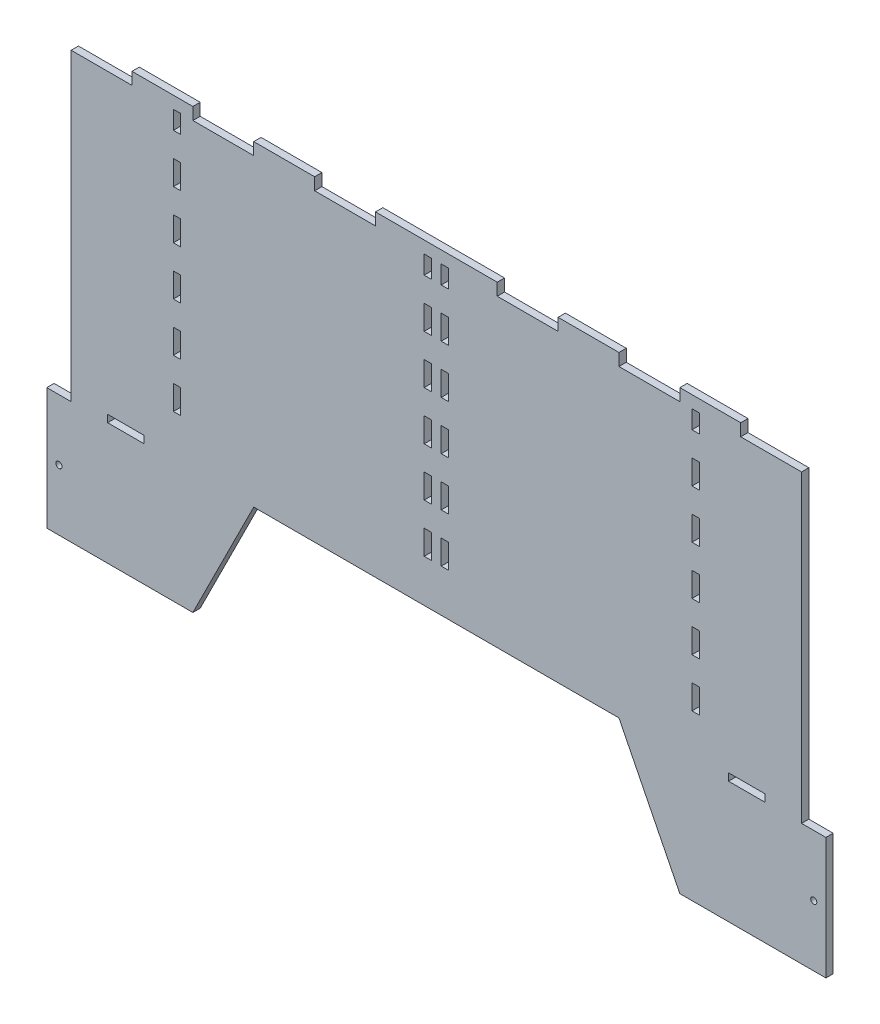
SolidWorks part; units mm, degrees
ref_plane "前视基准面" through (0, 0, 0) normal (0, 0, 1) x (1, 0, 0)
ref_plane "上视基准面" through (0, 0, 0) normal (0, 1, 0) x (1, 0, 0)
ref_plane "右视基准面" through (0, 0, 0) normal (1, 0, 0) x (0, 0, -1)
sketch "草图1" plane through (0, 0, 0) normal (0, 0, 1) x (1, 0, 0)
  line L0 (0, 0) -> (600, 0)
  line L1 (0, 0) -> (0, -250)
  line L2 (600, 0) -> (600, -250)
  line L3 (0, -250) -> (0, -350)
  line L4 (600, 0) -> (550, 0)
  line L5 (550, 0) -> (550, 10)
  line L6 (550, 10) -> (500, 10)
  line L7 (500, 10) -> (500, 0)
  line L8 (500, 0) -> (450, 0)
  line L9 (450, 0) -> (450, 10)
  line L10 (450, 10) -> (400, 10)
  line L11 (400, 10) -> (400, 0)
  line L12 (400, 0) -> (350, 0)
  line L13 (350, 0) -> (350, 10)
  line L14 (350, 10) -> (250, 10)
  line L15 (0, -350) -> (100, -350)
  line L16 (100, -350) -> (150, -250)
  line L17 (600, -250) -> (450, -250)
  line L18 (310, 0) -> (310, -250)
  line L19 (600, -300) -> (610, -300)
  line L20 (0, -250) -> (600, -250)
  line L21 (620, -350) -> (600, -350)
  line L22 (620, -250) -> (620, -350)
  line L23 (0, -250) -> (-20, -250)
  line L24 (510, 0) -> (510, -250)
  line L25 (310, -125) -> (304, -125)
  line L26 (84, -115) -> (84, -135)
  line L27 (84, -135) -> (84, -115)
  line L28 (304, -115) -> (304, -135)
  line L29 (304, -135) -> (304, -115)
  line L30 (304, -115) -> (310, -115)
  line L31 (310, -115) -> (310, -95)
  line L32 (310, -95) -> (304, -95)
  line L33 (304, -95) -> (304, -75)
  line L34 (304, -75) -> (310, -75)
  line L35 (310, -75) -> (310, -55)
  line L36 (310, -55) -> (304, -55)
  line L37 (304, -55) -> (304, -35)
  line L38 (304, -35) -> (310, -35)
  line L39 (310, -35) -> (310, -15)
  line L40 (310, -15) -> (304, -15)
  line L41 (304, -15) -> (304, 0)
  line L42 (84, -115) -> (90, -115)
  line L43 (90, -115) -> (90, -95)
  line L44 (90, -95) -> (84, -95)
  line L45 (304, -215) -> (310, -215)
  line L46 (304, -195) -> (304, -215)
  line L47 (310, -195) -> (304, -195)
  line L48 (310, -175) -> (310, -195)
  line L49 (304, -175) -> (310, -175)
  line L50 (304, -155) -> (304, -175)
  line L51 (310, -155) -> (304, -155)
  line L52 (310, -135) -> (310, -155)
  line L53 (304, -135) -> (310, -135)
  line L54 (310, 0) -> (510, 0)
  line L55 (84, -95) -> (84, -75)
  line L56 (84, -75) -> (90, -75)
  line L57 (90, -75) -> (90, -55)
  line L58 (516, -135) -> (510, -135)
  line L59 (510, -135) -> (510, -155)
  line L60 (510, -155) -> (516, -155)
  line L61 (516, -155) -> (516, -175)
  line L62 (516, -175) -> (510, -175)
  line L63 (510, -175) -> (510, -195)
  line L64 (510, -195) -> (516, -195)
  line L65 (516, -195) -> (516, -215)
  line L66 (516, -215) -> (510, -215)
  line L67 (90, -55) -> (84, -55)
  line L68 (84, -55) -> (84, -35)
  line L69 (84, -35) -> (90, -35)
  line L70 (516, -15) -> (516, 0)
  line L71 (510, -15) -> (516, -15)
  line L72 (510, -35) -> (510, -15)
  line L73 (516, -35) -> (510, -35)
  line L74 (516, -55) -> (516, -35)
  line L75 (510, -55) -> (516, -55)
  line L76 (510, -75) -> (510, -55)
  line L77 (516, -75) -> (510, -75)
  line L78 (516, -95) -> (516, -75)
  line L79 (510, -95) -> (516, -95)
  line L80 (510, -115) -> (510, -95)
  line L81 (516, -115) -> (510, -115)
  line L82 (516, -135) -> (516, -115)
  line L83 (516, -115) -> (516, -135)
  line L84 (90, -35) -> (90, -15)
  line L85 (90, -15) -> (84, -15)
  line L86 (84, -15) -> (84, 0)
  line L87 (84, -215) -> (90, -215)
  line L88 (84, -195) -> (84, -215)
  line L89 (90, -195) -> (84, -195)
  line L90 (90, -175) -> (90, -195)
  line L91 (84, -175) -> (90, -175)
  line L92 (84, -155) -> (84, -175)
  line L93 (90, -155) -> (84, -155)
  line L94 (90, -135) -> (90, -155)
  line L95 (84, -135) -> (90, -135)
  line L96 (290, 0) -> (90, 0)
  line L97 (296, -135) -> (290, -135)
  line L98 (290, -135) -> (290, -155)
  line L99 (290, -155) -> (296, -155)
  line L100 (296, -155) -> (296, -175)
  line L101 (296, -175) -> (290, -175)
  line L102 (290, -175) -> (290, -195)
  line L103 (290, -195) -> (296, -195)
  line L104 (296, -195) -> (296, -215)
  line L105 (296, -215) -> (290, -215)
  line L106 (296, -15) -> (296, 0)
  line L107 (290, -15) -> (296, -15)
  line L108 (290, -35) -> (290, -15)
  line L109 (296, -35) -> (290, -35)
  line L110 (296, -55) -> (296, -35)
  line L111 (290, -55) -> (296, -55)
  line L112 (290, -75) -> (290, -55)
  line L113 (296, -75) -> (290, -75)
  line L114 (296, -95) -> (296, -75)
  line L115 (290, -95) -> (296, -95)
  line L116 (290, -115) -> (290, -95)
  line L117 (296, -115) -> (290, -115)
  line L118 (296, -135) -> (296, -115)
  line L119 (296, -115) -> (296, -135)
  line L120 (290, -125) -> (296, -125)
  line L121 (90, 0) -> (90, -250)
  line L122 (-20, -250) -> (-20, -350)
  line L123 (-20, -350) -> (0, -350)
  line L124 (290, 0) -> (290, -250)
  line L125 (0, -300) -> (-10, -300)
  line L126 (250, 0) -> (250, 10)
  line L127 (200, 0) -> (250, 0)
  line L128 (200, 10) -> (200, 0)
  line L129 (150, 10) -> (200, 10)
  line L130 (150, 0) -> (150, 10)
  line L131 (100, 0) -> (150, 0)
  line L132 (100, 10) -> (100, 0)
  line L133 (50, 10) -> (100, 10)
  line L134 (50, 0) -> (50, 10)
  line L135 (0, 0) -> (50, 0)
  line L136 (300, 10) -> (300, 3.4241)
  line L137 (500, -350) -> (450, -250)
  line L138 (600, -350) -> (500, -350)
  line L139 (570, -250) -> (570, -244)
  line L140 (600, -250) -> (600, -350)
  line L141 (620, -250) -> (600, -250)
  line L143 (540, -250) -> (570, -250)
  line L146 (30, -244) -> (60, -244)
  line L147 (60, -244) -> (60, -250)
  line L148 (60, -250) -> (30, -250)
  line L149 (30, -250) -> (30, -244)
  line L150 (540, -244) -> (540, -250)
  line L151 (570, -244) -> (540, -244)
  circle A0 centre (-10, -300) radius 2.5
  circle A1 centre (610, -300) radius 2.5
extrude "凸台-拉伸1" add sketch "草图1" along normal blind 6
